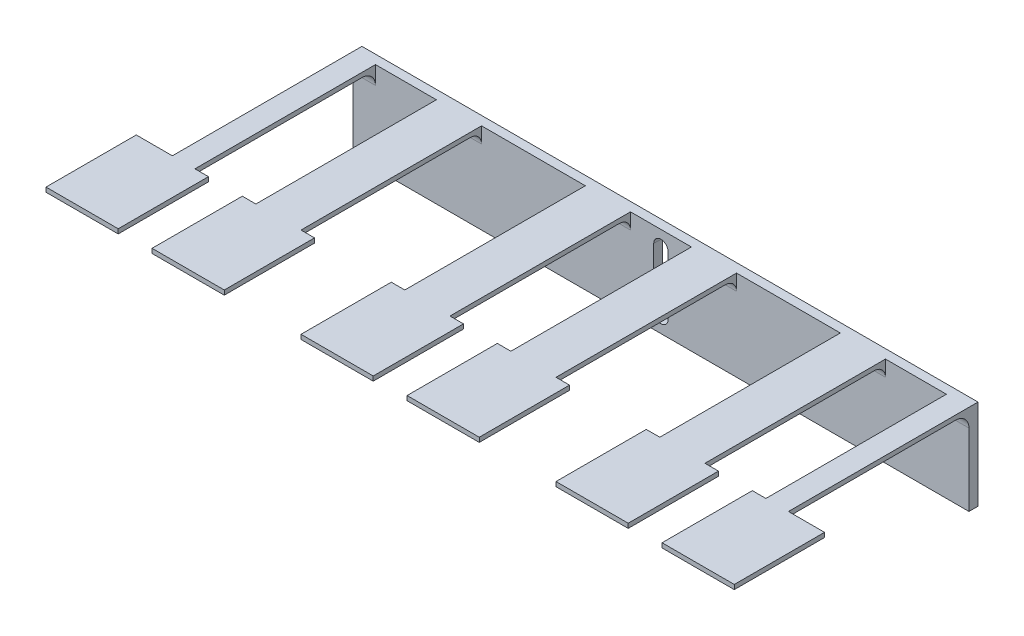
SolidWorks part; units mm, degrees
ref_plane "Front Plane" through (0, 0, 0) normal (0, 0, 1) x (1, 0, 0)
ref_plane "Top Plane" through (0, 0, 0) normal (0, 1, 0) x (1, 0, 0)
ref_plane "Right Plane" through (0, 0, 0) normal (1, 0, 0) x (0, 0, -1)
sketch "Sketch1" plane through (0, 0, 0) normal (0, 0, 1) x (1, 0, 0)
  line L1 (-1783.1561, 826.5671) -> (-1636.6561, 826.5671)
  line L2 (-1783.1561, 826.5671) -> (-1783.1561, 806.5671)
  line L3 (-1783.1561, 806.5671) -> (-1636.6561, 806.5671)
  line L4 (-1636.6561, 826.5671) -> (-1636.6561, 806.5671)
  dimension "D1" = 146.5
  dimension "D2" = 20
extrude "Boss-Extrude1" add sketch "Sketch1" along normal blind 2
sketch "Sketch2" plane through (0, 0, 2) normal (0, 0, 1) x (1, 0, 0)
  line L0 (-1636.6561, 826.5671) -> (-1783.1561, 826.5671) construction
  line L1 (-1783.1561, 826.5671) -> (-1773.1561, 826.5671)
  line L2 (-1783.1561, 826.5671) -> (-1783.1561, 825.5671)
  line L3 (-1783.1561, 825.5671) -> (-1773.1561, 825.5671)
  line L4 (-1773.1561, 826.5671) -> (-1773.1561, 825.5671)
  line L5 (-1778.1561, 825.5671) -> (-1778.1561, 826.5671) construction
  line L6 (-1783.1561, 826.5671) -> (-1783.1561, 806.5671) construction
  line L7 (-1754.6561, 825.5671) -> (-1754.6561, 826.5671) construction
  line L12 (-1759.6561, 826.5671) -> (-1749.6561, 826.5671)
  line L13 (-1759.6561, 826.5671) -> (-1759.6561, 825.5671)
  line L14 (-1759.6561, 825.5671) -> (-1749.6561, 825.5671)
  line L15 (-1749.6561, 826.5671) -> (-1749.6561, 825.5671)
  line L16 (-1641.6561, 825.5671) -> (-1641.6561, 826.5671) construction
  line L18 (-1646.6561, 826.5671) -> (-1636.6561, 826.5671)
  line L19 (-1646.6561, 826.5671) -> (-1646.6561, 825.5671)
  line L20 (-1646.6561, 825.5671) -> (-1636.6561, 825.5671)
  line L21 (-1636.6561, 826.5671) -> (-1636.6561, 825.5671)
  line L22 (-1636.6561, 806.5671) -> (-1636.6561, 826.5671) construction
  line L23 (-1665.1561, 825.5671) -> (-1665.1561, 826.5671) construction
  line L24 (-1660.1561, 826.5671) -> (-1670.1561, 826.5671)
  line L25 (-1660.1561, 826.5671) -> (-1660.1561, 825.5671)
  line L26 (-1660.1561, 825.5671) -> (-1670.1561, 825.5671)
  line L27 (-1670.1561, 826.5671) -> (-1670.1561, 825.5671)
  line L28 (-1709.9061, 806.5671) -> (-1709.9061, 826.5671) construction
  line L29 (-1783.1561, 806.5671) -> (-1636.6561, 806.5671) construction
  line L30 (-1721.6561, 825.5671) -> (-1721.6561, 826.5671) construction
  line L31 (-1726.6561, 826.5671) -> (-1716.6561, 826.5671)
  line L32 (-1726.6561, 826.5671) -> (-1726.6561, 825.5671)
  line L33 (-1726.6561, 825.5671) -> (-1716.6561, 825.5671)
  line L34 (-1716.6561, 826.5671) -> (-1716.6561, 825.5671)
  line L35 (-1698.1561, 825.5671) -> (-1698.1561, 826.5671) construction
  line L36 (-1703.1561, 826.5671) -> (-1693.1561, 826.5671)
  line L37 (-1703.1561, 826.5671) -> (-1703.1561, 825.5671)
  line L38 (-1703.1561, 825.5671) -> (-1693.1561, 825.5671)
  line L39 (-1693.1561, 826.5671) -> (-1693.1561, 825.5671)
  dimension "D1" = 10
  dimension "D2" = 1
  dimension "D3" = 5
  dimension "D4" = 10
  dimension "D5" = 23.5
  dimension "D6" = 10
  dimension "D7" = 1
  dimension "D8" = 5
  dimension "D9" = 10
  dimension "D10" = 23.5
  dimension "D11" = 10
  dimension "D12" = 11.75
  dimension "D13" = 10
  dimension "D14" = 11.75
extrude "Boss-Extrude2" add sketch "Sketch2" along normal blind 60
sketch "Sketch3" plane through (-1783.1561, 0, 0) normal (-1, 0, 0) x (0, 0, 1)
  line L0 (62, 825.5671) -> (2, 825.5671) construction
  line L1 (62, 826.5671) -> (42, 826.5671)
  line L2 (62, 826.5671) -> (62, 825.5671)
  line L3 (62, 825.5671) -> (42, 825.5671)
  line L4 (42, 826.5671) -> (42, 825.5671)
  dimension "D1" = 20
extrude "Boss-Extrude3" add sketch "Sketch3" along normal blind 3
sketch "Sketch4" plane through (-1773.1561, 0, 0) normal (1, 0, 0) x (0, 0, -1)
  line L6 (-62, 826.5671) -> (-42, 826.5671)
  line L7 (-62, 826.5671) -> (-62, 825.5671)
  line L8 (-62, 825.5671) -> (-42, 825.5671)
  line L9 (-42, 826.5671) -> (-42, 825.5671)
extrude "Boss-Extrude4" add sketch "Sketch4" along normal blind 3
sketch "Sketch5" plane through (-1759.6561, 0, 0) normal (-1, 0, 0) x (0, 0, 1)
  line L1 (42, 826.5671) -> (62, 826.5671)
  line L2 (42, 826.5671) -> (42, 825.5671)
  line L3 (42, 825.5671) -> (62, 825.5671)
  line L4 (62, 826.5671) -> (62, 825.5671)
extrude "Boss-Extrude5" add sketch "Sketch5" along normal blind 3 and the other way blind 13
sketch "Sketch6" plane through (-1749.6561, 0, 0) normal (1, 0, 0) x (0, 0, -1)
  line L0 (-62, 825.5671) -> (-2, 825.5671) construction
  line L1 (-62, 826.5671) -> (-32, 826.5671)
  line L2 (-62, 826.5671) -> (-62, 825.5671)
  line L3 (-62, 825.5671) -> (-32, 825.5671)
  line L4 (-32, 826.5671) -> (-32, 825.5671)
sketch "Sketch7" plane through (-1726.6561, 0, 0) normal (-1, 0, 0) x (0, 0, 1)
  line L1 (42, 826.5671) -> (62, 826.5671)
  line L2 (42, 826.5671) -> (42, 825.5671)
  line L3 (42, 825.5671) -> (62, 825.5671)
  line L4 (62, 826.5671) -> (62, 825.5671)
extrude "Boss-Extrude7" add sketch "Sketch7" along normal blind 3 and the other way blind 13
sketch "Sketch8" plane through (-1716.6561, 0, 0) normal (1, 0, 0) x (0, 0, -1)
  line L0 (-62, 825.5671) -> (-2, 825.5671) construction
  line L1 (-62, 826.5671) -> (-32, 826.5671)
  line L2 (-62, 826.5671) -> (-62, 825.5671)
  line L3 (-62, 825.5671) -> (-32, 825.5671)
  line L4 (-32, 826.5671) -> (-32, 825.5671)
sketch "Sketch9" plane through (-1703.1561, 0, 0) normal (-1, 0, 0) x (0, 0, 1)
  line L1 (42, 826.5671) -> (62, 826.5671)
  line L2 (42, 826.5671) -> (42, 825.5671)
  line L3 (42, 825.5671) -> (62, 825.5671)
  line L4 (62, 826.5671) -> (62, 825.5671)
extrude "Boss-Extrude9" add sketch "Sketch9" along normal blind 3 and the other way blind 13
sketch "Sketch10" plane through (-1693.1561, 0, 0) normal (1, 0, 0) x (0, 0, -1)
  line L0 (-62, 825.5671) -> (-2, 825.5671) construction
  line L1 (-62, 826.5671) -> (-32, 826.5671)
  line L2 (-62, 826.5671) -> (-62, 825.5671)
  line L3 (-62, 825.5671) -> (-32, 825.5671)
  line L4 (-32, 826.5671) -> (-32, 825.5671)
sketch "Sketch11" plane through (-1670.1561, 0, 0) normal (-1, 0, 0) x (0, 0, 1)
  line L1 (62, 826.5671) -> (42, 826.5671)
  line L2 (62, 826.5671) -> (62, 825.5671)
  line L3 (62, 825.5671) -> (42, 825.5671)
  line L4 (42, 826.5671) -> (42, 825.5671)
extrude "Boss-Extrude11" add sketch "Sketch11" along normal blind 3 and the other way blind 13
sketch "Sketch12" plane through (-1660.1561, 0, 0) normal (1, 0, 0) x (0, 0, -1)
  line L0 (-62, 825.5671) -> (-2, 825.5671) construction
  line L1 (-62, 826.5671) -> (-32, 826.5671)
  line L2 (-62, 826.5671) -> (-62, 825.5671)
  line L3 (-62, 825.5671) -> (-32, 825.5671)
  line L4 (-32, 826.5671) -> (-32, 825.5671)
sketch "Sketch13" plane through (-1636.6561, 0, 0) normal (1, 0, 0) x (0, 0, -1)
  line L0 (-62, 825.5671) -> (-2, 825.5671) construction
  line L1 (-62, 826.5671) -> (-32, 826.5671)
  line L2 (-62, 826.5671) -> (-62, 825.5671)
  line L3 (-62, 825.5671) -> (-32, 825.5671)
  line L4 (-32, 826.5671) -> (-32, 825.5671)
extrude "Boss-Extrude13" add sketch "Sketch13" along normal blind 3
sketch "Sketch14" plane through (-1646.6561, 0, 0) normal (-1, 0, 0) x (0, 0, 1)
  line L1 (42, 826.5671) -> (62, 826.5671)
  line L2 (42, 826.5671) -> (42, 825.5671)
  line L3 (42, 825.5671) -> (62, 825.5671)
  line L4 (62, 826.5671) -> (62, 825.5671)
extrude "Boss-Extrude14" add sketch "Sketch14" along normal blind 3
sketch "Sketch15" plane through (0, 0, 2) normal (0, 0, 1) x (1, 0, 0)
  line L0 (-1709.9061, 826.5671) -> (-1709.9061, 806.5671) construction
  line L1 (-1703.1561, 826.5671) -> (-1716.6561, 826.5671) construction
  line L2 (-1783.1561, 806.5671) -> (-1636.6561, 806.5671) construction
  line L3 (-1709.9061, 810.0671) -> (-1709.9061, 823.0671) construction
  line L4 (-1711.5061, 810.0671) -> (-1711.5061, 823.0671)
  line L5 (-1708.3061, 810.0671) -> (-1708.3061, 823.0671)
  arc A0 (-1711.5061, 810.0671) -> (-1708.3061, 810.0671) centre (-1709.9061, 810.0671) ccw
  arc A1 (-1708.3061, 823.0671) -> (-1711.5061, 823.0671) centre (-1709.9061, 823.0671) ccw
  point P8 (-1709.9061, 816.5671)
  dimension "D2" = 1.6
  dimension "D1" = 3.5
extrude "Cut-Extrude1" cut sketch "Sketch15" against normal blind 3
sketch "Sketch16" plane through (0, 0, 2) normal (0, 0, 1) x (1, 0, 0)
  line L0 (-1770.1561, 826.5671) -> (-1786.1561, 826.5671) construction
  line L9 (-1783.1561, 806.5671) -> (-1778.1561, 806.5671)
  line L10 (-1783.1561, 806.5671) -> (-1783.1561, 826.5671)
  line L11 (-1783.1561, 826.5671) -> (-1778.1561, 826.5671)
  line L12 (-1778.1561, 806.5671) -> (-1778.1561, 826.5671)
  line L13 (-1633.6561, 826.5671) -> (-1649.6561, 826.5671) construction
  line L14 (-1636.6561, 806.5671) -> (-1641.6561, 806.5671)
  line L15 (-1636.6561, 806.5671) -> (-1636.6561, 826.5671)
  line L16 (-1636.6561, 826.5671) -> (-1641.6561, 826.5671)
  line L17 (-1641.6561, 806.5671) -> (-1641.6561, 826.5671)
  dimension "D1" = 5
  dimension "D2" = 5
extrude "Cut-Extrude2" cut sketch "Sketch16" against normal blind 10
sketch "Sketch17" plane through (0, 825.5671, 0) normal (0, -1, 0) x (1, 0, 0)
  line L0 (-1633.6561, 62) -> (-1633.6561, 32) construction
  line L1 (-1783.1561, 42) -> (-1778.1561, 42)
  line L2 (-1783.1561, 42) -> (-1783.1561, 2)
  line L3 (-1783.1561, 2) -> (-1778.1561, 2)
  line L4 (-1778.1561, 42) -> (-1778.1561, 2)
  line L9 (-1641.6561, 2) -> (-1633.6561, 2)
  line L10 (-1641.6561, 2) -> (-1641.6561, 42)
  line L11 (-1641.6561, 42) -> (-1633.6561, 42)
  line L12 (-1633.6561, 2) -> (-1633.6561, 42)
extrude "Cut-Extrude3" cut sketch "Sketch17" against normal blind 10
fillet "Fillet1" radius 3 2 edges at (-1644.1561, 825.5671, 2) (-1775.6561, 825.5671, 2)
fillet "Fillet2" radius 2.5 4 edges at (-1754.6561, 825.5671, 2) (-1721.6561, 825.5671, 2) (-1698.1561, 825.5671, 2) (-1665.1561, 825.5671, 2)
